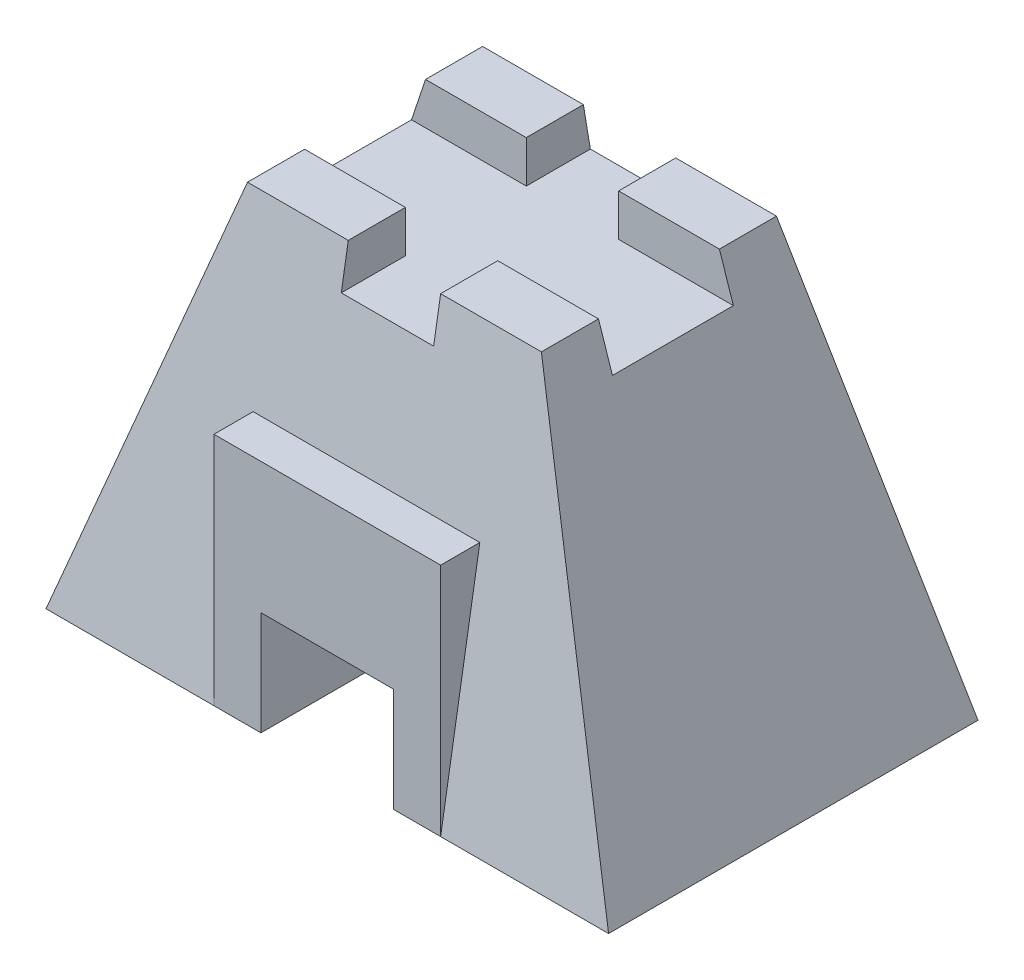
SolidWorks part; units mm, degrees
ref_plane "Alzado" through (0, 0, 0) normal (0, 0, 1) x (1, 0, 0)
ref_plane "Planta" through (0, 0, 0) normal (0, 1, 0) x (1, 0, 0)
ref_plane "Vista lateral" through (0, 0, 0) normal (1, 0, 0) x (0, 0, -1)
sketch "Croquis2" plane through (0, 0, 0) normal (0, 1, 0) x (1, 0, 0)
  line L1 (212.725, -139.7) -> (-212.725, -139.7)
  line L2 (212.725, -139.7) -> (212.725, 139.7)
  line L3 (212.725, 139.7) -> (-212.725, 139.7)
  line L4 (-212.725, -139.7) -> (-212.725, 139.7)
  line L5 (212.725, -139.7) -> (-212.725, 139.7) construction
  line L6 (212.725, 139.7) -> (-212.725, -139.7) construction
  point P0 (0, 0)
  dimension "D1" = 425.45
  dimension "D2" = 279.4
ref_plane "Plano1" through (0, 304.8, 0) normal (0, 1, 0) x (1, 0, 0)
sketch "Croquis3" plane through (0, 304.8, 0) normal (0, 1, 0) x (1, 0, 0)
  line L5 (111.125, -88.9) -> (-111.125, -88.9)
  line L6 (111.125, -88.9) -> (111.125, 88.9)
  line L7 (111.125, 88.9) -> (-111.125, 88.9)
  line L8 (-111.125, -88.9) -> (-111.125, 88.9)
  line L9 (111.125, -88.9) -> (-111.125, 88.9) construction
  line L10 (111.125, 88.9) -> (-111.125, -88.9) construction
  point P0 (0, 0)
  dimension "D1" = 222.25
  dimension "D2" = 177.8
loft "Recubrir1" add profiles "Croquis2", "Croquis3"
sketch "Croquis5" plane through (0, 304.8, 0) normal (0, 1, 0) x (1, 0, 0)
  line L0 (-111.125, 88.9) -> (-111.125, -88.9) construction
  line L1 (171.9213, -45.72) -> (34.925, -45.72)
  line L2 (171.9213, -45.72) -> (171.9213, 45.72)
  line L3 (171.9213, 45.72) -> (34.925, 45.72)
  line L4 (-171.9213, -45.72) -> (-171.9213, 45.72)
  line L5 (34.925, 45.72) -> (34.925, 107.2296)
  line L6 (-34.925, -45.72) -> (-171.9213, -45.72)
  line L7 (34.925, -107.2296) -> (-34.925, -107.2296)
  line L8 (34.925, -107.2296) -> (34.925, -45.72)
  line L9 (34.925, 107.2296) -> (-34.925, 107.2296)
  line L10 (-34.925, -107.2296) -> (-34.925, -45.72)
  line L13 (111.125, 88.9) -> (-111.125, 88.9) construction
  line L15 (-34.925, 45.72) -> (-34.925, 107.2296)
  line L18 (-34.925, 45.72) -> (-171.9213, 45.72)
  point P0 (0, 0)
  point P6 (0, 0)
  dimension "D1" = 76.2
  dimension "D2" = 43.18
extrude "Cortar-Extruir3" cut sketch "Croquis5" against normal blind 31.75
ref_plane "Plano2" through (-212.725, 0, 0) normal (1, 0, 0) x (0, 0, -1)
sketch "Croquis6" plane through (-212.725, 0, 0) normal (1, 0, 0) x (0, 0, -1)
  line L0 (139.7, 0) -> (0, 144.78)
  line L1 (0, 144.78) -> (-139.7, 0)
  line L2 (-139.7, 0) -> (139.7, 0)
  line L3 (0, 144.78) -> (0, 0) construction
  dimension "D1" = 144.78
extrude "Saliente-Extruir1" add sketch "Croquis6" along normal up to surface (48.26 mm away)
ref_plane "Plano3" through (0, 0, 139.7) normal (0, 0, 1) x (1, 0, 0)
sketch "Croquis7" plane through (0, 0, 139.7) normal (0, 0, 1) x (1, 0, 0)
  line L0 (-212.725, 0) -> (212.725, 0) construction
  line L1 (-85.725, 0) -> (85.725, 0)
  line L2 (-85.725, 0) -> (-85.725, 177.8)
  line L3 (-85.725, 177.8) -> (85.725, 177.8)
  line L4 (85.725, 0) -> (85.725, 177.8)
  line L5 (-212.725, 144.78) -> (-212.725, 0) construction
  dimension "D1" = 127
  dimension "D2" = 177.8
  dimension "D3" = 171.45
extrude "Saliente-Extruir2" add sketch "Croquis7" against normal up to surface
sketch "Croquis8" plane through (0, 0, 139.7) normal (0, 0, 1) x (1, 0, 0)
  line L0 (-85.725, 0) -> (85.725, 0) construction
  line L1 (-50.165, 0) -> (50.165, 0)
  line L2 (-50.165, 0) -> (-50.165, 78.74)
  line L3 (-50.165, 78.74) -> (50.165, 78.74)
  line L4 (50.165, 0) -> (50.165, 78.74)
  line L5 (-85.725, 177.8) -> (-85.725, 0) construction
  line L6 (85.725, 0) -> (85.725, 177.8) construction
  dimension "D1" = 35.56
  dimension "D2" = 78.74
  dimension "D3" = 35.56
extrude "Cortar-Extruir4" cut sketch "Croquis8" against normal up to surface (279.4 mm away)
